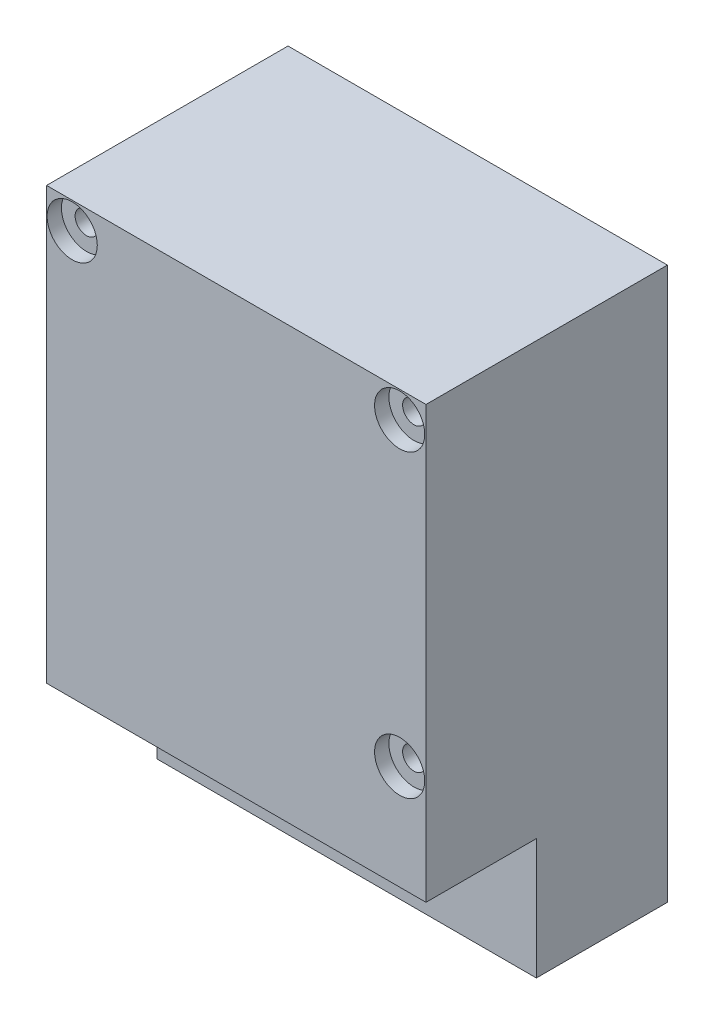
SolidWorks part; units mm, degrees
ref_plane "前视基准面" through (0, 0, 0) normal (0, 0, 1) x (1, 0, 0)
ref_plane "上视基准面" through (0, 0, 0) normal (0, 1, 0) x (1, 0, 0)
ref_plane "右视基准面" through (0, 0, 0) normal (1, 0, 0) x (0, 0, -1)
other "Configuration Table"
sketch "草图1" plane through (0, 0, 0) normal (0, 0, 1) x (1, 0, 0)
  line L1 (-55, 80) -> (55, 80)
  line L2 (-55, 80) -> (-55, -80)
  line L3 (-55, -80) -> (55, -80)
  line L4 (55, 80) -> (55, -80)
  line L5 (-55, 80) -> (55, -80) construction
  line L6 (-55, -80) -> (55, 80) construction
  point P0 (0, 0)
extrude "凸台-拉伸1" add sketch "草图1" along normal blind 70 contours L2 L1 L4 L3
sketch "草图2" plane through (0, -80, 0) normal (0, -1, 0) x (1, 0, 0)
  line L1 (-55, 70) -> (55, 70)
  line L2 (-55, 70) -> (-55, 50)
  line L3 (-55, 50) -> (55, 50)
  line L4 (55, 70) -> (55, 50)
extrude "切除-拉伸1" cut sketch "草图2" against normal blind 35
sketch "草图9" plane through (0, -80, 0) normal (0, -1, 0) x (1, 0, 0)
  line L0 (55, 50) -> (55, 0) construction
  line L1 (-55, 50) -> (55, 50)
  line L2 (-55, 50) -> (-55, 38)
  line L3 (-55, 38) -> (55, 38)
  line L4 (55, 50) -> (55, 38)
extrude "切除-拉伸2" cut sketch "草图9" against normal blind 35
hole_wizard "M6 六角头螺钉的柱形沉头孔1" positions "草图14" profile "草图13" counterbore size "M6" standard "ANSI Metric" end condition through all
sketch "草图14" plane through (0, 0, 70) normal (0, 0, 1) x (1, 0, 0)
  point P0 (-47.5707, 72.3237)
  point P2 (47.3669, 72.3237)
  point P4 (47.3669, -14.6685)
sketch "草图13" plane through (-47.5707, 72.3237, 70) normal (1, 0, 0) x (0, -1, 0)
  line L0 (0, 0) -> (0, 70)
  line L1 (0, 70) -> (3.3, 70)
  line L3 (3.3, 70) -> (3.3, 4.15)
  line L4 (3.3, 4.15) -> (7.275, 4.15)
  line L5 (7.275, 4.15) -> (7.275, 0)
  line L7 (7.275, 0) -> (0, 0)
  line L11 (0, -6.35) -> (0, 107.95) construction
  dimension "通孔孔直径" = 6.6
  dimension "通孔孔深度" = 70
  dimension "柱形沉头孔直径" = 14.55
  dimension "柱形沉头孔深度" = 4.15
